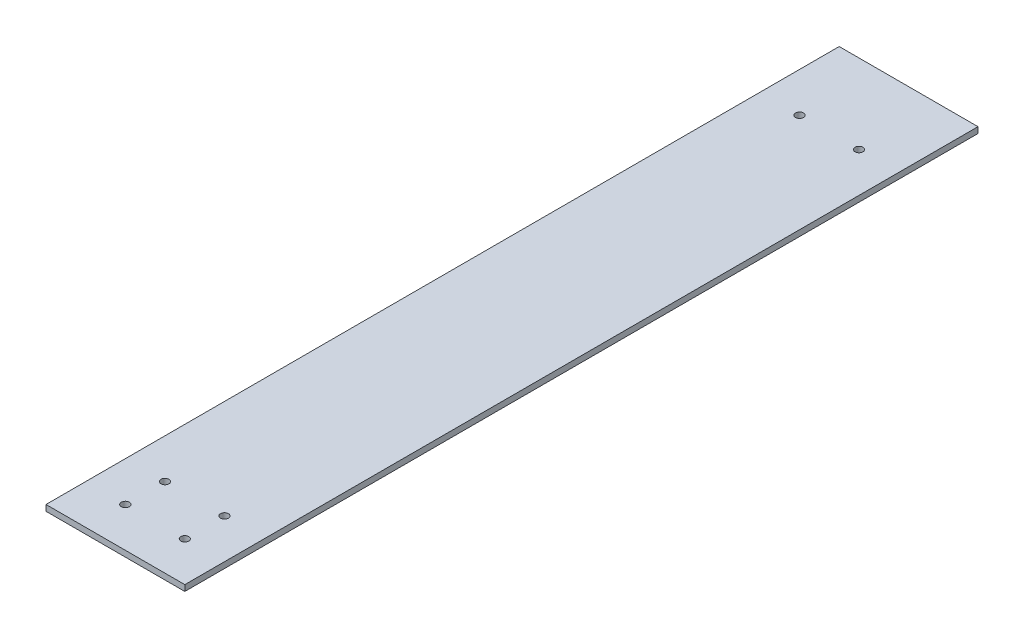
SolidWorks part; units mm, degrees
ref_plane "Alzado" through (0, 0, 0) normal (0, 0, 1) x (1, 0, 0)
ref_plane "Planta" through (0, 0, 0) normal (0, 1, 0) x (1, 0, 0)
ref_plane "Vista lateral" through (0, 0, 0) normal (1, 0, 0) x (0, 0, -1)
sketch "Croquis2" plane through (0, 0, 0) normal (0, 1, 0) x (1, 0, 0)
  line L0 (-99.0392, 362.9368) -> (-99.0392, -37.0632)
  line L1 (-99.0392, 362.9368) -> (-29.0392, 362.9368)
  line L2 (-99.0392, -37.0632) -> (-29.0392, -37.0632)
  line L3 (-29.0392, 362.9368) -> (-29.0392, -37.0632)
  dimension "D1" = 70
  dimension "D2" = 400
extrude "Saliente-Extruir1" add sketch "Croquis2" along normal blind 3
sketch "Croquis3" plane through (0, 3, 0) normal (0, 1, 0) x (1, 0, 0)
  line L0 (-29.0392, 362.9368) -> (-99.0392, 362.9368) construction
  line L1 (-99.0392, 362.9368) -> (-99.0392, -37.0632) construction
  line L2 (-29.0392, -37.0632) -> (-29.0392, 362.9368) construction
  line L3 (-99.0392, -37.0632) -> (-29.0392, -37.0632) construction
  circle A0 centre (-79.0392, 322.9368) radius 2
  circle A1 centre (-49.0392, 322.9368) radius 2
  circle A2 centre (-79.0392, 2.9368) radius 2
  circle A3 centre (-49.0392, 2.9368) radius 2
  circle A4 centre (-79.0392, -17.0632) radius 2
  circle A5 centre (-49.0392, -17.0632) radius 2
  dimension "D1" = 4
  dimension "D2" = 40
  dimension "D3" = 20
  dimension "D4" = 4
  dimension "D5" = 20
  dimension "D6" = 40
  dimension "D7" = 40
  dimension "D8" = 20
  dimension "D9" = 20
  dimension "D10" = 20
  dimension "D11" = 20
  dimension "D12" = 20
  dimension "D13" = 20
extrude "Cortar-Extruir1" cut sketch "Croquis3" against normal through all
